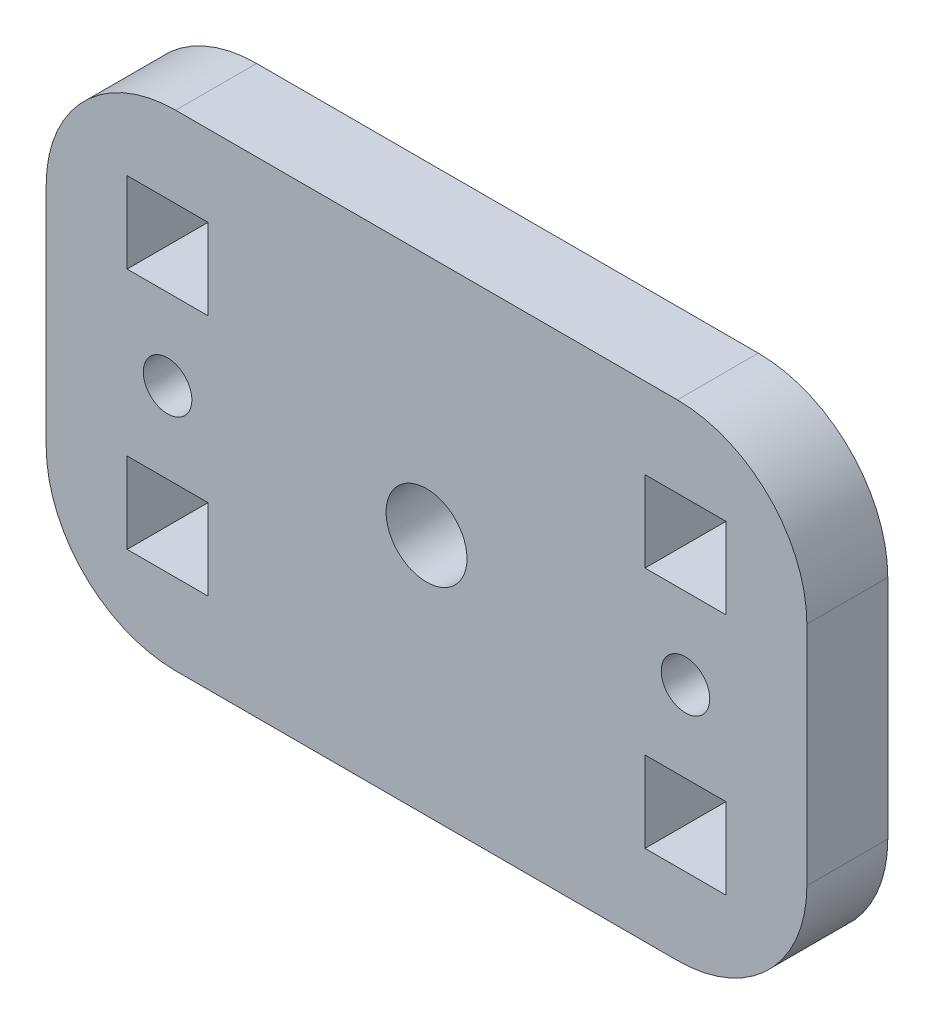
SolidWorks part; units mm, degrees
ref_plane "Plan de face" through (0, 0, 0) normal (0, 0, 1) x (1, 0, 0)
ref_plane "Plan de dessus" through (0, 0, 0) normal (0, 1, 0) x (1, 0, 0)
ref_plane "Plan de droite" through (0, 0, 0) normal (1, 0, 0) x (0, 0, -1)
sketch "Esquisse1" plane through (0, 0, 0) normal (0, 0, 1) x (1, 0, 0)
  line L0 (0, 15) -> (47, 15) construction
  line L1 (8, 0) -> (39, 0)
  line L2 (0, 8) -> (0, 22)
  line L3 (8, 30) -> (39, 30)
  line L4 (47, 8) -> (47, 22)
  line L5 (5, 25) -> (10, 25)
  line L6 (5, 25) -> (5, 20)
  line L7 (5, 20) -> (10, 20)
  line L8 (10, 25) -> (10, 20)
  line L17 (37, 25) -> (42, 25)
  line L18 (37, 25) -> (37, 20)
  line L19 (37, 20) -> (42, 20)
  line L20 (42, 25) -> (42, 20)
  line L21 (42, 5) -> (42, 10)
  line L22 (37, 10) -> (42, 10)
  line L23 (37, 5) -> (37, 10)
  line L24 (37, 5) -> (42, 5)
  line L33 (10, 5) -> (10, 10)
  line L34 (5, 10) -> (10, 10)
  line L35 (5, 5) -> (5, 10)
  line L36 (5, 5) -> (10, 5)
  line L37 (39.5, 20) -> (39.5, 10) construction
  line L38 (7.5, 20) -> (7.5, 10) construction
  arc A0 (8, 0) -> (0, 8) centre (8, 8) cw
  arc A1 (39, 0) -> (47, 8) centre (39, 8) ccw
  arc A2 (39, 30) -> (47, 22) centre (39, 22) cw
  arc A3 (0, 22) -> (8, 30) centre (8, 22) cw
  circle A4 centre (7.5, 15) radius 1.5
  circle A5 centre (39.5, 15) radius 1.5
  circle A8 centre (23.5, 15) radius 2.5
  point P7 (0, 0)
  point P12 (47, 30)
  point P15 (0, 30)
  point P20 (0, 0)
  point P21 (0, 0)
  point P22 (0, 0)
  point P40 (0, 0)
  dimension "D3" = 8
  dimension "D10" = 10
  dimension "D13" = 3
  dimension "D9" = 3
  dimension "D8" = 5
  dimension "D2" = 37
  dimension "D4" = 5
  dimension "D5" = 5
  dimension "D6" = 5
  dimension "D7" = 5
  dimension "D11" = 5
extrude "Boss.-Extru.1" add sketch "Esquisse1" along normal blind 5
